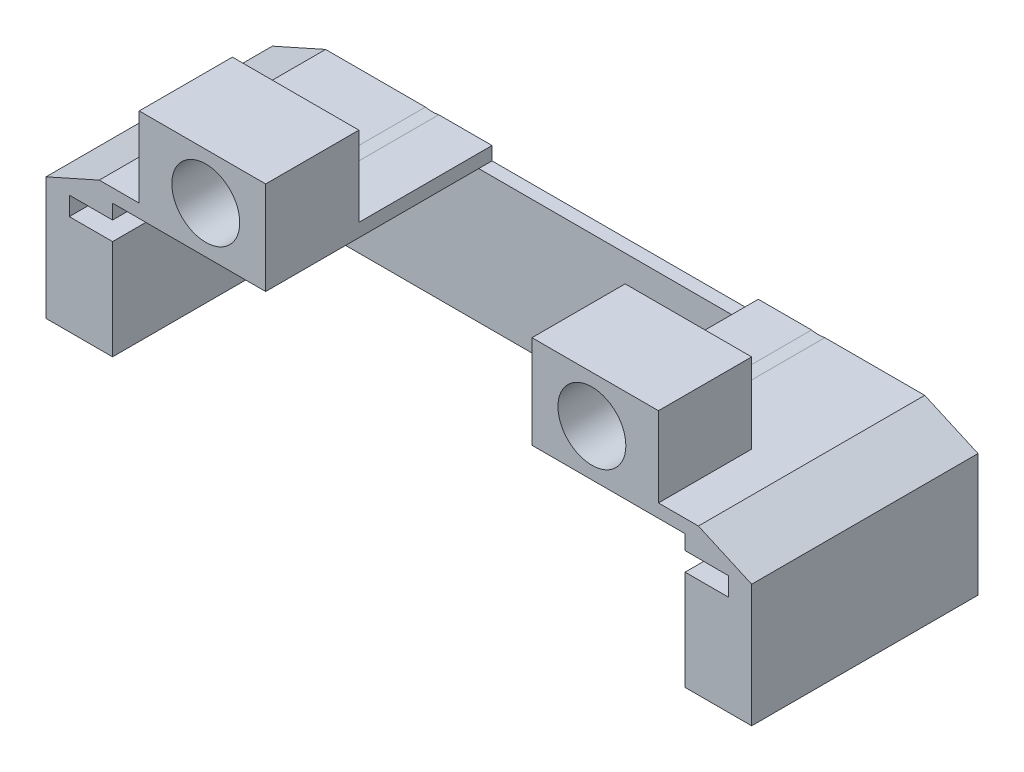
SolidWorks part; units mm, degrees
ref_plane "Alzado" through (0, 0, 0) normal (0, 0, 1) x (1, 0, 0)
ref_plane "Planta" through (0, 0, 0) normal (0, 1, 0) x (1, 0, 0)
ref_plane "Vista lateral" through (0, 0, 0) normal (1, 0, 0) x (0, 0, -1)
sketch "Croquis1" plane through (0, 0, 0) normal (0, 0, 1) x (1, 0, 0)
  line L1 (-54.908, 27.1123) -> (-3.908, 27.1123)
  line L2 (-54.908, 27.1123) -> (-54.908, 10.1123)
  line L3 (-54.908, 10.1123) -> (-3.908, 10.1123)
  line L4 (-3.908, 27.1123) -> (-3.908, 10.1123)
  dimension "D1" = 51
  dimension "D2" = 17
extrude "Saliente-Extruir1" add sketch "Croquis1" along normal blind 17
sketch "Croquis2" plane through (0, 10.1123, 0) normal (0, -1, 0) x (1, 0, 0)
  line L1 (-54.908, 17) -> (-3.908, 17) construction
  line L4 (-36.908, 17) -> (-21.908, 17)
  line L5 (-36.908, 17) -> (-36.908, 1)
  line L6 (-36.908, 1) -> (-21.908, 1)
  line L7 (-21.908, 17) -> (-21.908, 1)
extrude "Cortar-Extruir1" cut sketch "Croquis2" against normal up to vertex (17 mm away)
sketch "Croquis3" plane through (0, 0, 17) normal (0, 0, 1) x (1, 0, 0)
  line L0 (-36.908, 27.1123) -> (-54.908, 27.1123) construction
  line L1 (-54.908, 10.1123) -> (-36.908, 10.1123) construction
  line L3 (-50.908, 10.1123) -> (-7.908, 10.1123)
  line L4 (-50.908, 10.1123) -> (-50.908, 20.1123)
  line L5 (-50.908, 20.1123) -> (-7.908, 20.1123)
  line L6 (-7.908, 10.1123) -> (-7.908, 20.1123)
  dimension "D1" = 4
  dimension "D2" = 4
  dimension "D3" = 7
extrude "Cortar-Extruir2" cut sketch "Croquis3" against normal up to vertex (16 mm away)
sketch "Croquis5" plane through (0, 0, 17) normal (0, 0, 1) x (1, 0, 0)
  circle A0 centre (-43.908, 23.6123) radius 2.55
  circle A1 centre (-14.908, 23.6123) radius 2.55
  dimension "D4" = 29
extrude "Cortar-Extruir3" cut sketch "Croquis5" against normal up to vertex
sketch "Croquis6" plane through (0, 0, 17) normal (0, 0, 1) x (1, 0, 0)
  line L2 (-54.908, 27.1123) -> (-54.908, 10.1123) construction
  line L3 (-4.658, 17.6123) -> (-54.158, 17.6123)
  line L4 (-4.658, 17.6123) -> (-4.658, 19.0123)
  line L5 (-4.658, 19.0123) -> (-54.158, 19.0123)
  line L6 (-54.158, 17.6123) -> (-54.158, 19.0123)
  line L7 (-3.908, 10.1123) -> (-3.908, 27.1123) construction
  dimension "D1" = 0.75
  dimension "D2" = 0.75
  dimension "D3" = 1.4
extrude "Cortar-Extruir4" cut sketch "Croquis6" against normal up to vertex (16 mm away)
sketch "Croquis7" plane through (0, 0, 17) normal (0, 0, 1) x (1, 0, 0)
  line L0 (-36.908, 20.1123) -> (-50.908, 20.1123) construction
  line L1 (-3.908, 27.1123) -> (-9.908, 27.1123)
  line L2 (-3.908, 27.1123) -> (-3.908, 21.1123)
  line L3 (-3.908, 21.1123) -> (-9.908, 21.1123)
  line L4 (-9.908, 27.1123) -> (-9.908, 21.1123)
  line L5 (-54.908, 27.1123) -> (-48.908, 27.1123)
  line L6 (-54.908, 27.1123) -> (-54.908, 21.1123)
  line L7 (-54.908, 21.1123) -> (-48.908, 21.1123)
  line L8 (-48.908, 27.1123) -> (-48.908, 21.1123)
  line L9 (-39.408, 27.1123) -> (-39.408, 20.1123)
  line L15 (-3.908, 27.1123) -> (-21.908, 27.1123) construction
  line L16 (-7.908, 20.1123) -> (-21.908, 20.1123) construction
  line L17 (-39.408, 27.1123) -> (-19.408, 27.1123)
  line L19 (-39.408, 20.1123) -> (-19.408, 20.1123)
  line L20 (-19.408, 27.1123) -> (-19.408, 20.1123)
extrude "Cortar-Extruir5" cut sketch "Croquis7" against normal up to vertex
sketch "Croquis8" plane through (-9.908, 0, 0) normal (1, 0, 0) x (0, 0, -1)
  line L0 (0, 27.1123) -> (-17, 27.1123) construction
  line L1 (0, 21.1123) -> (-10, 21.1123)
  line L2 (0, 21.1123) -> (0, 27.1123)
  line L3 (0, 27.1123) -> (-10, 27.1123)
  line L4 (-10, 21.1123) -> (-10, 27.1123)
  dimension "D1" = 10
extrude "Cortar-Extruir6" cut sketch "Croquis8" against normal up to vertex
sketch "Croquis10" plane through (-54.908, 0, 0) normal (-1, 0, 0) x (0, 0, 1)
  line L0 (0, 21.1123) -> (17, 21.1123)
  line L1 (17, 21.1123) -> (17, 10.1123)
  line L2 (17, 10.1123) -> (0, 10.1123)
  line L3 (0, 10.1123) -> (0, 21.1123)
extrude "Saliente-Extruir4" add sketch "Croquis10" along normal blind 1
sketch "Croquis11" plane through (-3.908, 0, 0) normal (1, 0, 0) x (0, 0, -1)
  line L0 (-17, 10.1123) -> (0, 10.1123)
  line L1 (0, 10.1123) -> (0, 21.1123)
  line L2 (0, 21.1123) -> (-17, 21.1123)
  line L3 (-17, 21.1123) -> (-17, 10.1123)
extrude "Saliente-Extruir5" add sketch "Croquis11" along normal blind 1
sketch "Croquis12" plane through (0, 0, 17) normal (0, 0, 1) x (1, 0, 0)
  line L0 (-55.908, 21.1123) -> (-51.908, 21.1123)
  line L1 (-55.908, 21.1123) -> (-48.908, 21.1123) construction
  line L2 (-55.908, 21.1123) -> (-55.908, 19.326)
  line L3 (-55.908, 10.1123) -> (-55.908, 21.1123) construction
  line L4 (-55.908, 19.326) -> (-51.908, 21.1123)
  line L5 (-2.908, 21.1123) -> (-6.908, 21.1123)
  line L6 (-9.908, 21.1123) -> (-2.908, 21.1123) construction
  line L7 (-2.908, 21.1123) -> (-2.908, 19.326)
  line L8 (-2.908, 21.1123) -> (-2.908, 10.1123) construction
  line L9 (-6.908, 21.1123) -> (-2.908, 19.326)
  dimension "D1" = 1
  dimension "D2" = 1
extrude "Cortar-Extruir7" cut sketch "Croquis12" against normal up to vertex
